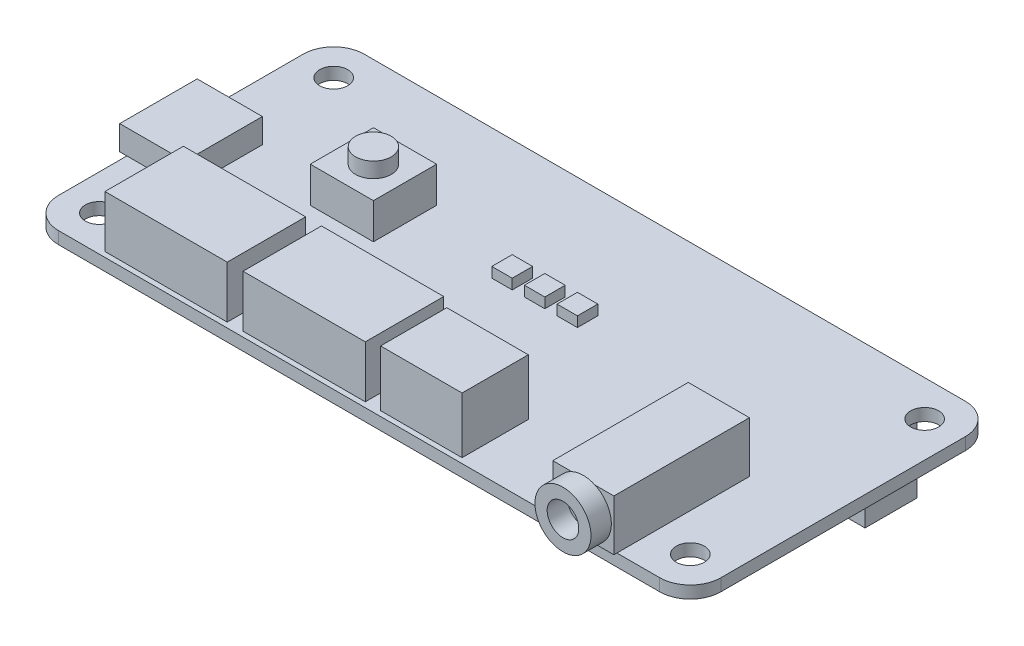
SolidWorks part; units mm, degrees
ref_plane "前视基准面" through (0, 0, 0) normal (0, 0, 1) x (1, 0, 0)
ref_plane "上视基准面" through (0, 0, 0) normal (0, 1, 0) x (1, 0, 0)
ref_plane "右视基准面" through (0, 0, 0) normal (1, 0, 0) x (0, 0, -1)
sketch "草图1" plane through (0, 0, 0) normal (0, 1, 0) x (1, 0, 0)
  line L1 (-29.5, 15) -> (29.5, 15)
  line L2 (-32.5, 12) -> (-32.5, -12)
  line L3 (-29.5, -15) -> (29.5, -15)
  line L4 (32.5, 12) -> (32.5, -12)
  line L5 (-32.5, 15) -> (32.5, -15) construction
  line L6 (-32.5, -15) -> (32.5, 15) construction
  arc A0 (29.5, 15) -> (32.5, 12) centre (29.5, 12) cw
  arc A1 (29.5, -15) -> (32.5, -12) centre (29.5, -12) ccw
  arc A2 (-32.5, -12) -> (-29.5, -15) centre (-29.5, -12) ccw
  arc A3 (-29.5, 15) -> (-32.5, 12) centre (-29.5, 12) ccw
  point P0 (0, 0)
  dimension "D3" = 3
  dimension "D1" = 65
  dimension "D2" = 30
extrude "凸台-拉伸1" add sketch "草图1" along normal blind 1.2
sketch "草图2" plane through (0, 1.2, 0) normal (0, 1, 0) x (1, 0, 0)
  line L0 (-29.5, -15) -> (29.5, -15) construction
  line L1 (32.5, -12) -> (32.5, 12) construction
  line L2 (29.5, 15) -> (-29.5, 15) construction
  circle A0 centre (29, -11.5) radius 1.375
  circle A1 centre (29, 11.5) radius 1.375
  circle A2 centre (-29, -11.5) radius 1.375
  circle A3 centre (-29, 11.5) radius 1.375
  dimension "D1" = 2.75
  dimension "D2" = 3.5
  dimension "D3" = 3.5
  dimension "D4" = 3.5
  dimension "D5" = 3.5
extrude "切除-拉伸1" cut sketch "草图2" against normal blind 1.2
sketch "草图3" plane through (0, 1.2, 0) normal (0, 1, 0) x (1, 0, 0)
  line L0 (-29.5, -15) -> (29.5, -15) construction
  line L1 (25.3, -15) -> (19.3, -15)
  line L2 (25.3, -15) -> (25.3, -2)
  line L3 (25.3, -2) -> (19.3, -2)
  line L4 (19.3, -15) -> (19.3, -2)
  line L5 (32.5, -12) -> (32.5, 12) construction
  dimension "D1" = 13
  dimension "D2" = 6
  dimension "D3" = 7.2
extrude "凸台-拉伸2" add sketch "草图3" along normal blind 5
sketch "草图4" plane through (0, 0, 15) normal (0, 0, 1) x (1, 0, 0)
  line L1 (19.3, 1.2) -> (25.3, 1.2)
  line L2 (19.3, 1.2) -> (19.3, 6.2)
  line L3 (19.3, 6.2) -> (25.3, 6.2)
  line L4 (25.3, 1.2) -> (25.3, 6.2)
extrude "凸台-拉伸3" add sketch "草图4" along normal blind 0.3
sketch "草图5" plane through (0, 1.2, 0) normal (0, 1, 0) x (1, 0, 0)
  line L0 (32.5, -12) -> (32.5, 12) construction
  line L1 (9.6, -8) -> (1.6, -8)
  line L2 (9.6, -8) -> (9.6, -15)
  line L3 (9.6, -15) -> (1.6, -15)
  line L4 (1.6, -8) -> (1.6, -15)
  line L5 (-29.5, -15) -> (19.3, -15) construction
  dimension "D1" = 22.9
  dimension "D2" = 7
  dimension "D3" = 8
extrude "凸台-拉伸4" add sketch "草图5" along normal blind 5.5
sketch "草图6" plane through (0, 1.2, 0) normal (0, 1, 0) x (1, 0, 0)
  line L0 (-29.5, -15) -> (1.6, -15) construction
  line L1 (0.1, -15) -> (-11.9, -15)
  line L2 (0.1, -15) -> (0.1, -6.8)
  line L3 (0.1, -6.8) -> (-11.9, -6.8)
  line L4 (-11.9, -15) -> (-11.9, -6.8)
  dimension "D1" = 8.2
  dimension "D2" = 12
  dimension "D3" = 1.5
extrude "凸台-拉伸5" add sketch "草图6" along normal blind 5.1
sketch "草图7" plane through (0, 1.2, 0) normal (0, 1, 0) x (1, 0, 0)
  line L0 (-29.5, -15) -> (-11.9, -15) construction
  line L1 (-13.45, -15) -> (-25.45, -15)
  line L2 (-13.45, -15) -> (-13.45, -6.8)
  line L3 (-13.45, -6.8) -> (-25.45, -6.8)
  line L4 (-25.45, -15) -> (-25.45, -6.8)
  dimension "D1" = 12
  dimension "D2" = 8.2
  dimension "D3" = 1.55
extrude "凸台-拉伸6" add sketch "草图7" along normal blind 5.1
sketch "草图8" plane through (0, 1.2, 0) normal (0, 1, 0) x (1, 0, 0)
  line L0 (-32.5, 12) -> (-32.5, -12) construction
  line L1 (-32.5, -5.3) -> (-26.8, -5.3)
  line L2 (-32.5, -5.3) -> (-32.5, 2.3)
  line L3 (-32.5, 2.3) -> (-26.8, 2.3)
  line L4 (-26.8, -5.3) -> (-26.8, 2.3)
  line L5 (-29.5, -15) -> (-25.45, -15) construction
  dimension "D1" = 9.7
  dimension "D2" = 7.6
  dimension "D3" = 5.7
extrude "凸台-拉伸7" add sketch "草图8" along normal blind 2.4
sketch "草图9" plane through (-32.5, 0, 0) normal (-1, 0, 0) x (0, 0, 1)
  line L1 (-2.3, 3.6) -> (5.3, 3.6)
  line L2 (-2.3, 3.6) -> (-2.3, 1.2)
  line L3 (-2.3, 1.2) -> (5.3, 1.2)
  line L4 (5.3, 3.6) -> (5.3, 1.2)
extrude "凸台-拉伸8" add sketch "草图9" along normal blind 0.7
sketch "草图10" plane through (0, 0, 15) normal (0, 0, 1) x (1, 0, 0)
  line L1 (-25.45, 6.3) -> (-13.45, 6.3)
  line L2 (-25.45, 6.3) -> (-25.45, 1.2)
  line L3 (-25.45, 1.2) -> (-13.45, 1.2)
  line L4 (-13.45, 6.3) -> (-13.45, 1.2)
  line L5 (-11.9, 6.3) -> (0.1, 6.3)
  line L6 (-11.9, 6.3) -> (-11.9, 1.2)
  line L7 (-11.9, 1.2) -> (0.1, 1.2)
  line L8 (0.1, 6.3) -> (0.1, 1.2)
  line L9 (1.6, 6.7) -> (9.6, 6.7)
  line L10 (1.6, 6.7) -> (1.6, 1.2)
  line L11 (1.6, 1.2) -> (9.6, 1.2)
  line L12 (9.6, 6.7) -> (9.6, 1.2)
extrude "切除-拉伸2" cut sketch "草图10" against normal blind 0.5
sketch "草图11" plane through (0, 0, 0) normal (0, -1, 0) x (1, 0, 0)
  line L0 (29.5, -15) -> (-29.5, -15) construction
  line L1 (25.65, -14.1) -> (-25.75, -14.1)
  line L2 (25.65, -14.1) -> (25.65, -9)
  line L3 (25.65, -9) -> (-25.75, -9)
  line L4 (-25.75, -14.1) -> (-25.75, -9)
  line L5 (32.5, 12) -> (32.5, -12) construction
  dimension "D1" = 51.4
  dimension "D2" = 5.1
  dimension "D3" = 0.9
  dimension "D4" = 6.85
extrude "凸台-拉伸9" add sketch "草图11" along normal blind 8.5
sketch "草图12" plane through (0, 1.2, 0) normal (0, 1, 0) x (1, 0, 0)
  line L0 (-32.5, 12) -> (-32.5, 2.3) construction
  line L1 (-13.1, -0.5) -> (-19.3, -0.5)
  line L2 (-13.1, -0.5) -> (-13.1, 5.7)
  line L3 (-13.1, 5.7) -> (-19.3, 5.7)
  line L4 (-19.3, -0.5) -> (-19.3, 5.7)
  line L5 (29.5, 15) -> (-29.5, 15) construction
  dimension "D1" = 6.2
  dimension "D2" = 6.2
  dimension "D3" = 13.2
  dimension "D4" = 9.3
extrude "凸台-拉伸10" add sketch "草图12" along normal blind 3.5
sketch "草图13" plane through (0, 4.7, 0) normal (0, 1, 0) x (1, 0, 0)
  circle A0 centre (-16.2, 2.6) radius 1.75
  dimension "D1" = 3.5
extrude "凸台-拉伸11" add sketch "草图13" along normal blind 1.5
sketch "草图14" plane through (0, 1.2, 0) normal (0, 1, 0) x (1, 0, 0)
  line L0 (29.5, 15) -> (-29.5, 15) construction
  line L1 (4.2, 2.22) -> (2.2, 2.22)
  line L2 (4.2, 2.22) -> (4.2, 4.22)
  line L3 (4.2, 4.22) -> (2.2, 4.22)
  line L4 (2.2, 2.22) -> (2.2, 4.22)
  line L13 (1, 2.22) -> (-1, 2.22)
  line L14 (1, 2.22) -> (1, 4.22)
  line L15 (1, 4.22) -> (-1, 4.22)
  line L16 (-1, 2.22) -> (-1, 4.22)
  line L17 (-2.2, 2.22) -> (-4.2, 2.22)
  line L18 (-2.2, 2.22) -> (-2.2, 4.22)
  line L19 (-2.2, 4.22) -> (-4.2, 4.22)
  line L20 (-4.2, 2.22) -> (-4.2, 4.22)
  line L21 (32.5, -12) -> (32.5, 12) construction
  dimension "D1" = 2
  dimension "D2" = 2
  dimension "D3" = 1.2
  dimension "D4" = 1.2
  dimension "D5" = 10.78
  dimension "D6" = 28.3
extrude "凸台-拉伸12" add sketch "草图14" along normal blind 1
sketch "草图15" plane through (0, 0, 15.3) normal (0, 0, 1) x (1, 0, 0)
  circle A0 centre (22.3, 3.7) radius 1.55
  circle A1 centre (22.3, 3.7) radius 2.75
extrude "凸台-拉伸13" add sketch "草图15" along normal blind 2
